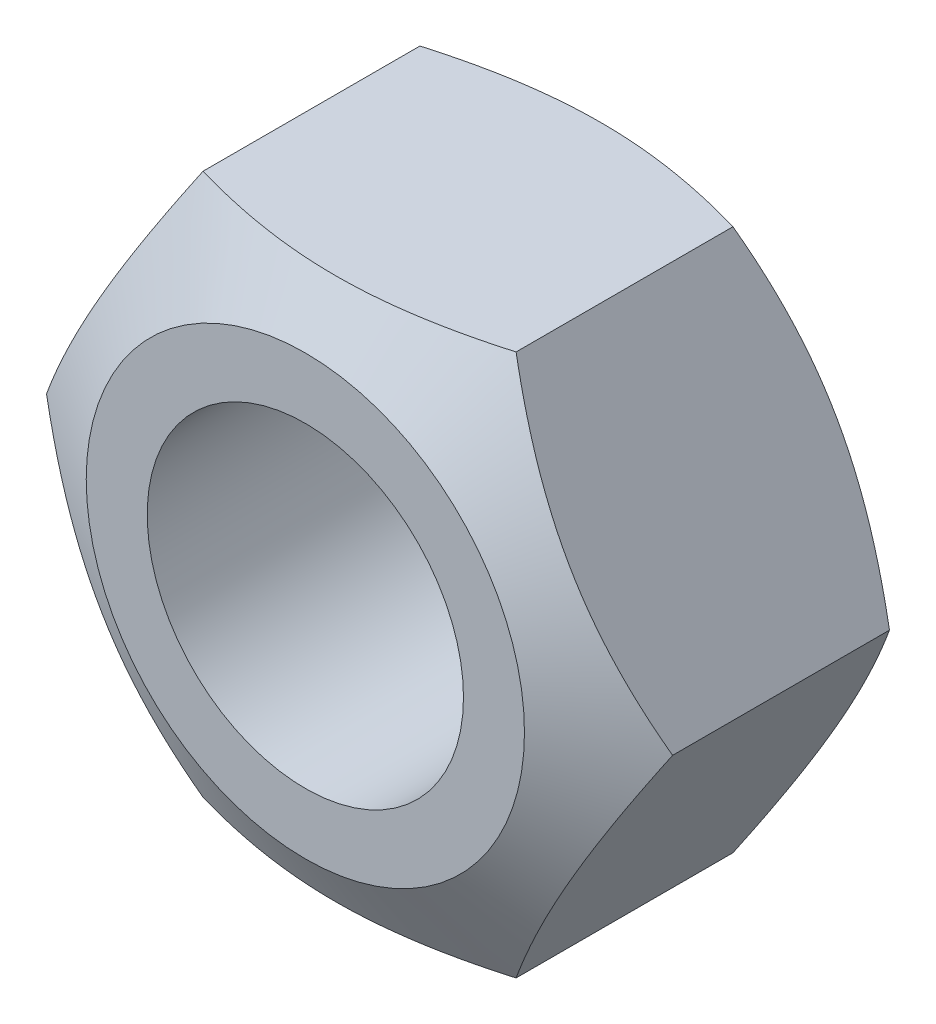
SolidWorks part; units mm, degrees
ref_plane "前视" through (0, 0, 0) normal (0, 0, 1) x (1, 0, 0)
ref_plane "上视" through (0, 0, 0) normal (0, 1, 0) x (1, 0, 0)
ref_plane "右视" through (0, 0, 0) normal (1, 0, 0) x (0, 0, -1)
sketch "草图1" plane through (0, 0, 0) normal (0, 0, 1) x (1, 0, 0)
  line L1 (17.3205, 0) -> (8.6603, 15)
  line L2 (8.6603, 15) -> (-8.6603, 15)
  line L3 (-8.6603, 15) -> (-17.3205, 0)
  line L4 (-17.3205, 0) -> (-8.6603, -15)
  line L5 (-8.6603, -15) -> (8.6603, -15)
  line L6 (8.6603, -15) -> (17.3205, 0)
  circle A0 centre (0, 0) radius 15 construction
  dimension "D1" = 30
extrude "拉伸1" add sketch "草图1" along normal blind 18
sketch "草图2" plane through (0, 0, 0) normal (0, 1, 0) x (1, 0, 0)
  line L0 (-18.9103, -3) -> (18.2967, -3) construction
  line L1 (-18.9103, -9) -> (18.2967, -9) construction
  line L2 (17.3205, -18) -> (17.3205, 0) construction
  line L3 (17.3205, -18) -> (17.3205, 0) construction
  line L4 (1.9004, 5.9028) -> (17.3205, -3)
  line L5 (17.3205, -3) -> (20.281, 2.1277)
  line L6 (20.281, 2.1277) -> (1.9004, 5.9028)
  line L7 (17.3205, -15) -> (20.281, -20.1277)
  line L8 (1.9004, -23.9028) -> (17.3205, -15)
  line L9 (20.281, -20.1277) -> (1.9004, -23.9028)
  line L10 (0, 13.3063) -> (0, -27.2012) construction
  dimension "D1" = 3
  dimension "D2" = 9
  dimension "D3" = 30
revolve "切除-旋转1" cut sketch "草图2" angle 360 about L10
hole_wizard "M20 螺纹孔1" positions "3D草图1" profile "草图3" tap size "M20" standard "ISO"
sketch3d "3D草图1"
  point P0 (0, 0, 18)
sketch "草图3" plane through (0, 0, 18) normal (1, 0, 0) x (0, -1, 0)
  line L0 (0, 0) -> (0, 52.7575)
  line L1 (0, 52.7575) -> (8.75, 47.5)
  line L2 (8.75, 47.5) -> (8.75, 0)
  line L5 (8.75, 0) -> (0, 0)
  line L10 (0, 52.7575) -> (-8.75, 47.5) construction
  line L11 (0, -6.35) -> (0, 107.95) construction
  dimension "蹟恇謂郰芛眻噤" = 17.5
  dimension "蹟恇謂郰芛旮僅" = 47.5
  dimension "絳芛褒僅" = 118
cosmetic thread "孔螺蚊线1" parameters "D1"=18, "D2"=20
